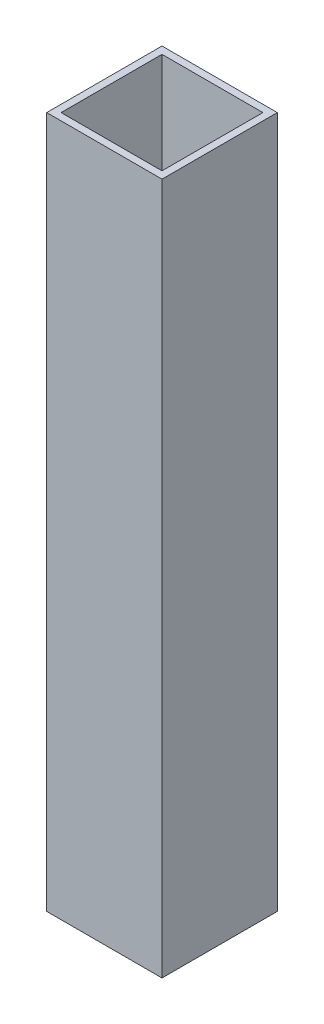
SolidWorks part; units mm, degrees
ref_plane "Front Plane" through (0, 0, 0) normal (0, 0, 1) x (1, 0, 0)
ref_plane "Top Plane" through (0, 0, 0) normal (0, 1, 0) x (1, 0, 0)
ref_plane "Right Plane" through (0, 0, 0) normal (1, 0, 0) x (0, 0, -1)
sketch "Sketch1" plane through (0, 0, 0) normal (0, 1, 0) x (1, 0, 0)
  line L1 (-12.7, -12.7) -> (12.7, -12.7)
  line L2 (-12.7, -12.7) -> (-12.7, 12.7)
  line L3 (-12.7, 12.7) -> (12.7, 12.7)
  line L4 (12.7, -12.7) -> (12.7, 12.7)
  line L5 (-12.7, -12.7) -> (12.7, 12.7) construction
  line L6 (-12.7, 12.7) -> (12.7, -12.7) construction
  line L7 (-11.1125, -11.1125) -> (11.1125, -11.1125)
  line L8 (-11.1125, -11.1125) -> (-11.1125, 11.1125)
  line L9 (-11.1125, 11.1125) -> (11.1125, 11.1125)
  line L10 (11.1125, -11.1125) -> (11.1125, 11.1125)
  line L11 (-11.1125, -11.1125) -> (11.1125, 11.1125) construction
  line L12 (-11.1125, 11.1125) -> (11.1125, -11.1125) construction
  point P0 (0, 0)
  point P6 (0, 0)
  dimension "D1" = 25.4
  dimension "D2" = 1.5875
extrude "Boss-Extrude1" add sketch "Sketch1" along normal blind 152.4
